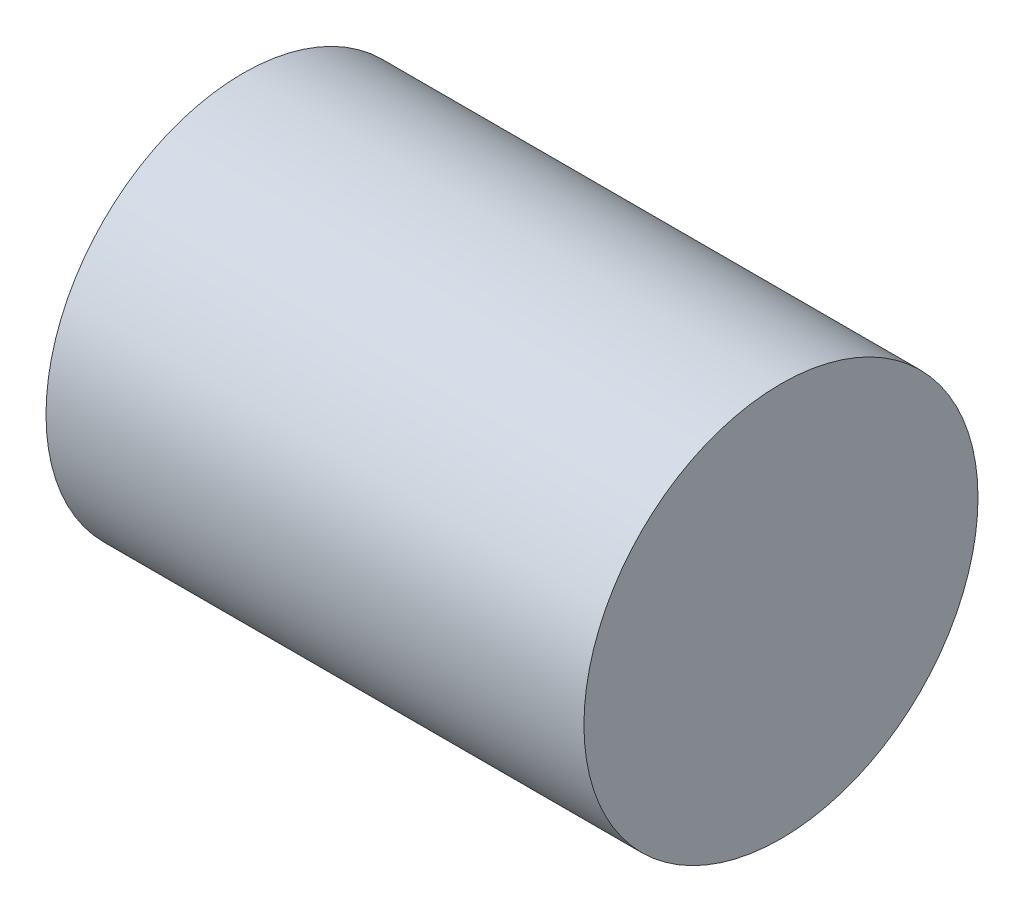
SolidWorks part; units mm, degrees
ref_plane "Front Plane" through (0, 0, 0) normal (0, 0, 1) x (1, 0, 0)
ref_plane "Top Plane" through (0, 0, 0) normal (0, 1, 0) x (1, 0, 0)
ref_plane "Right Plane" through (0, 0, 0) normal (1, 0, 0) x (0, 0, -1)
sketch "Sketch1" plane through (0, 0, 0) normal (1, 0, 0) x (0, 0, -1)
  circle A0 centre (0, 0) radius 16.002
  dimension "D1" = 32.004
extrude "Boss-Extrude1" add sketch "Sketch1" along normal mid plane 43.688
